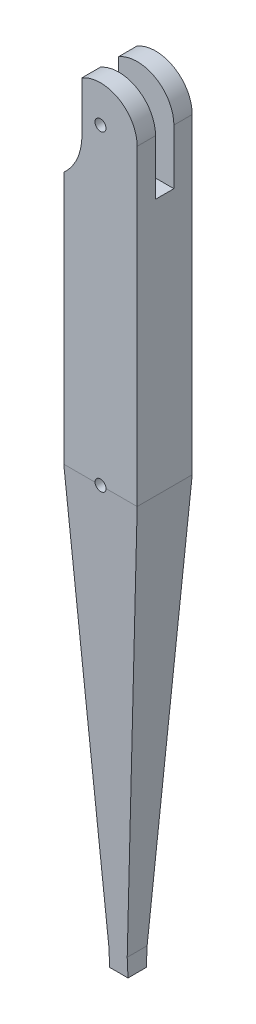
SolidWorks part; units mm, degrees
ref_plane "Alzado" through (0, 0, 0) normal (0, 0, 1) x (1, 0, 0)
ref_plane "Planta" through (0, 0, 0) normal (0, 1, 0) x (1, 0, 0)
ref_plane "Vista lateral" through (0, 0, 0) normal (1, 0, 0) x (0, 0, -1)
sketch "Croquis1" plane through (0, 0, 0) normal (0, 0, 1) x (1, 0, 0)
  line L0 (0, 0) -> (0, -200) construction
  line L1 (0, 0) -> (0, -200) construction
  line L2 (10, 0) -> (10, -85)
  line L3 (-10, 0) -> (-10, -85)
  line L4 (-2.497, -197.5) -> (-10, -85)
  line L5 (-2.497, -202.5) -> (2.497, -202.5)
  line L6 (-2.497, -202.5) -> (-2.497, -197.5)
  line L8 (2.497, -202.5) -> (2.497, -197.5)
  line L9 (-2.497, -202.5) -> (2.497, -197.5) construction
  line L10 (-2.497, -197.5) -> (2.497, -202.5) construction
  line L11 (2.497, -197.5) -> (10, -85)
  arc A0 (10, 0) -> (-10, 0) centre (0, 0) ccw
  circle A1 centre (0, -85) radius 1.5
  circle A2 centre (0, 0) radius 1.5
  point P3 (-5.9974, -73.809)
  point P10 (0, -200)
  dimension "D2" = 3
  dimension "D3" = 10
  dimension "D6" = 3
  dimension "D11" = 10
  dimension "D1" = 200
  dimension "D4" = 4.994
  dimension "D5" = 5
  dimension "D7" = 85
  dimension "D8" = 85
  dimension "D9" = 85
  dimension "D10" = 10
extrude "Saliente-Extruir1" add sketch "Croquis1" along normal blind 15
sketch "Croquis2" plane through (10, 0, 0) normal (1, 0, 0) x (0, 0, -1)
  line L0 (-15, 10) -> (0, 10) construction
  line L1 (-7.5, -202.5) -> (-7.5, -111.0206) construction
  line L2 (-10, -15) -> (-5, -15)
  line L3 (-10, -15) -> (-10, 35)
  line L4 (-10, 35) -> (-5, 35)
  line L5 (-5, -15) -> (-5, 35)
  line L6 (-10, -15) -> (-5, 35) construction
  line L7 (-10, 35) -> (-5, -15) construction
  line L8 (-15, -202.5) -> (0, -202.5) construction
  line L9 (-15, -85) -> (-10, -202.5)
  line L10 (-15, -85) -> (-18.0819, -208.0213)
  line L11 (-18.0819, -208.0213) -> (-10, -202.5)
  line L12 (0, -85) -> (3.0819, -208.0213)
  line L13 (0, -85) -> (-5, -202.5)
  line L14 (-5, -202.5) -> (3.0819, -208.0213)
  line L15 (3.0819, -208.0213) -> (2.641, -207.5803)
  point P4 (-7.5, 10)
  line M2 (0, 0) -> (-15, 0)
  dimension "D1" = 5
  dimension "D2" = 50
  dimension "D3" = 2.5
extrude "Cortar-Extruir1" cut sketch "Croquis2" against normal blind 60 contours L2 L5 L3 M2 | L5 L4 L3 M2 | L9 L11 L10 | L14 L13 L12
sketch "Croquis4" plane through (-10, 0, 0) normal (-1, 0, 0) x (0, 0, 1)
  line L0 (0, -85) -> (15, -85) construction
  line L2 (5, -100) -> (10, -100)
  line L3 (5, -100) -> (5, -70)
  line L4 (5, -70) -> (10, -70)
  line L5 (10, -100) -> (10, -70)
  line L6 (5, -100) -> (10, -70) construction
  line L7 (5, -70) -> (10, -100) construction
  point P4 (7.5, -85)
  dimension "D1" = 5
  dimension "D2" = 30
extrude "Cortar-Extruir2" cut sketch "Croquis4" against normal blind 15
sketch "Croquis5" plane through (0, 0, 0) normal (0, 0, -1) x (-1, 0, 0)
  line L1 (20.047, -20) -> (24.8746, -20)
  line L2 (10, 13.0634) -> (10, 14.4827)
  line L3 (10, 14.4827) -> (5.047, 14.4827)
  line L4 (5.047, -5) -> (5.047, 14.4827)
  line L8 (10, 13.0634) -> (24.8746, 13.0634)
  line L9 (24.8746, -20) -> (24.8746, 13.0634)
  arc A0 (20.047, -20) -> (5.047, -5) centre (20.047, -5) cw
  dimension "D1" = 15
extrude "Cortar-Extruir3" cut sketch "Croquis5" against normal blind 40
